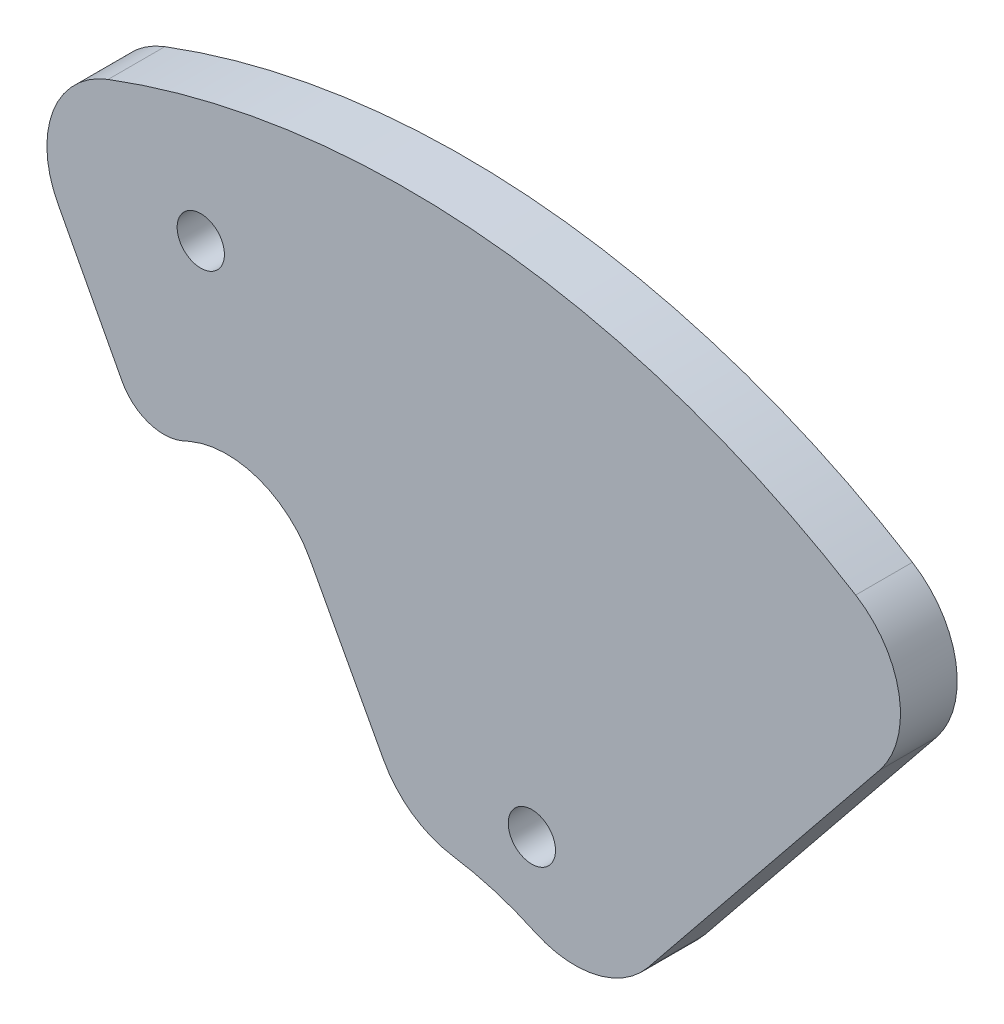
SolidWorks part; units mm, degrees
ref_plane "Plan de face" through (0, 0, 0) normal (0, 0, 1) x (1, 0, 0)
ref_plane "Plan de dessus" through (0, 0, 0) normal (0, 1, 0) x (1, 0, 0)
ref_plane "Plan de droite" through (0, 0, 0) normal (1, 0, 0) x (0, 0, -1)
sketch "Esquisse2" plane through (0, 0, 0) normal (0, 0, 1) x (1, 0, 0)
  line L0 (0, 0) -> (13.1118, 37.2603) construction
  line L1 (13.1118, 37.2603) -> (-21.9035, 74.3403) construction
  line L2 (-21.9035, 74.3403) -> (0, 0) construction
  line L3 (-37.0232, 70.2089) -> (-30.2293, 57.3253)
  line L4 (37.7025, 46.6746) -> (49.8758, 61.7447)
  line L5 (25.4315, 31.4835) -> (30.0979, 37.2603)
  line L6 (30.0979, 37.2603) -> (37.7025, 46.6746)
  line L7 (-2.5788, 36.4861) -> (-10.3398, 50.9233)
  circle A0 centre (0, 0) radius 90 construction
  circle A1 centre (0, 0) radius 60 construction
  circle A2 centre (13.1118, 37.2603) radius 2.5
  circle A3 centre (-21.9035, 74.3403) radius 2.5
  arc A4 (-31.6999, 84.2325) -> (47.3588, 76.532) centre (0, 0) cw
  arc A5 (13.4181, 28.708) -> (4.735, 31.3333) centre (0, 0) ccw
  arc A6 (-22.9773, 55.426) -> (-23.8214, 55.0685) centre (0, 0) ccw
  arc A7 (-37.0232, 70.2089) -> (-31.6999, 84.2325) centre (-28.1777, 74.8733) cw
  arc A8 (49.8758, 61.7447) -> (47.3588, 76.532) centre (42.0967, 68.0285) ccw
  arc A9 (13.4181, 28.708) -> (25.4315, 31.4835) centre (17.6524, 37.7672) ccw
  arc A10 (4.735, 31.3333) -> (-2.5788, 36.4861) centre (6.2292, 41.221) cw
  arc A11 (-10.3398, 50.9233) -> (-22.9773, 55.426) centre (-19.1477, 46.1883) ccw
  arc A12 (-30.2293, 57.3253) -> (-23.8214, 55.0685) centre (-25.8066, 59.6575) ccw
  point P20 (-41.9804, 79.6094)
  point P23 (56.5538, 70.0119)
  point P30 (-14.2909, 58.2732)
  dimension "D1" = 180
  dimension "D6" = 5
  dimension "D7" = 5
  dimension "D8" = 10
  dimension "D9" = 5
  dimension "D3" = 39.5
  dimension "D4" = 51
  dimension "D5" = 77.5
  dimension "D2" = 30
extrude "Boss.-Extru.1" add sketch "Esquisse2" along normal blind 6
